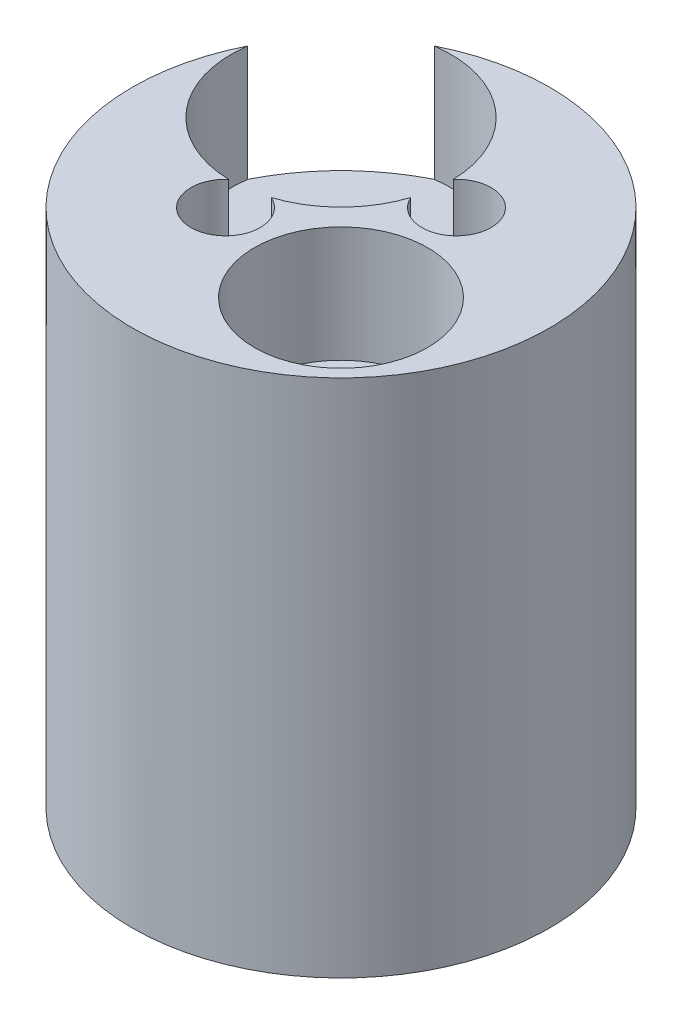
SolidWorks part; units mm, degrees
ref_plane "Front Plane" through (0, 0, 0) normal (0, 0, 1) x (1, 0, 0)
ref_plane "Top Plane" through (0, 0, 0) normal (0, 1, 0) x (1, 0, 0)
ref_plane "Right Plane" through (0, 0, 0) normal (1, 0, 0) x (0, 0, -1)
sketch "Sketch1" plane through (0, 0, 0) normal (0, 1, 0) x (1, 0, 0)
  circle A0 centre (0, 0) radius 91.7575
  dimension "D1" = 183.515
extrude "Boss-Extrude1" add sketch "Sketch1" along normal blind 228.6
sketch "Sketch2" plane through (0, 228.6, 0) normal (0, 1, 0) x (1, 0, 0)
  line L0 (-91.7575, 0) -> (91.7575, 0) construction
  line L1 (0, 91.7575) -> (0, -91.7575) construction
  circle A0 centre (0, 0) radius 91.7575 construction
  circle A1 centre (-34.29, 34.29) radius 48.26
  circle A2 centre (34.29, -34.29) radius 38.1
  dimension "D1" = 96.52
  dimension "D2" = 76.2
  dimension "D3" = 34.29
  dimension "D4" = 34.29
  dimension "D5" = 34.29
  dimension "D6" = 34.29
extrude "Cut-Extrude1" cut sketch "Sketch2" against normal blind 50.8
sketch "Sketch4" plane through (0, 228.6, 0) normal (0, 1, 0) x (1, 0, 0)
  line L0 (-91.7575, 0) -> (91.7575, 0) construction
  line L1 (0, 91.7575) -> (0, -91.7575) construction
  circle A0 centre (0, 0) radius 91.7575 construction
  circle A1 centre (25.4, 25.4) radius 15.24
  circle A2 centre (-25.4, -25.4) radius 15.24
  dimension "D1" = 30.48
  dimension "D2" = 30.48
  dimension "D3" = 25.4
  dimension "D4" = 25.4
  dimension "D5" = 25.4
  dimension "D6" = 25.4
extrude "Cut-Extrude2" cut sketch "Sketch4" against normal blind 177.8
sketch "Sketch5" plane through (0, 0, 0) normal (0, -1, 0) x (1, 0, 0)
  line L0 (-91.7575, 0) -> (91.7575, 0) construction
  line L1 (0, 91.7575) -> (0, -91.7575) construction
  circle A0 centre (0, 0) radius 91.7575 construction
  circle A1 centre (-25.4, -25.4) radius 15.24
  circle A2 centre (25.4, 25.4) radius 15.24
  dimension "D1" = 30.48
  dimension "D6" = 30.48
  dimension "D2" = 25.4
  dimension "D3" = 25.4
  dimension "D4" = 25.4
  dimension "D5" = 25.4
extrude "Cut-Extrude3" cut sketch "Sketch5" against normal blind 177.8
sketch "Sketch6" plane through (0, 0, 0) normal (0, -1, 0) x (1, 0, 0)
  line L0 (-91.7575, 0) -> (91.7575, 0) construction
  line L1 (0, 91.7575) -> (0, -91.7575) construction
  circle A0 centre (0, 0) radius 91.7575 construction
  circle A1 centre (-34.29, 34.29) radius 38.1
  circle A2 centre (34.29, -34.29) radius 38.1
  dimension "D1" = 76.2
  dimension "D2" = 76.2
  dimension "D3" = 34.29
  dimension "D4" = 34.29
  dimension "D5" = 34.29
  dimension "D6" = 34.29
extrude "Cut-Extrude9" cut sketch "Sketch6" against normal blind 50.8
